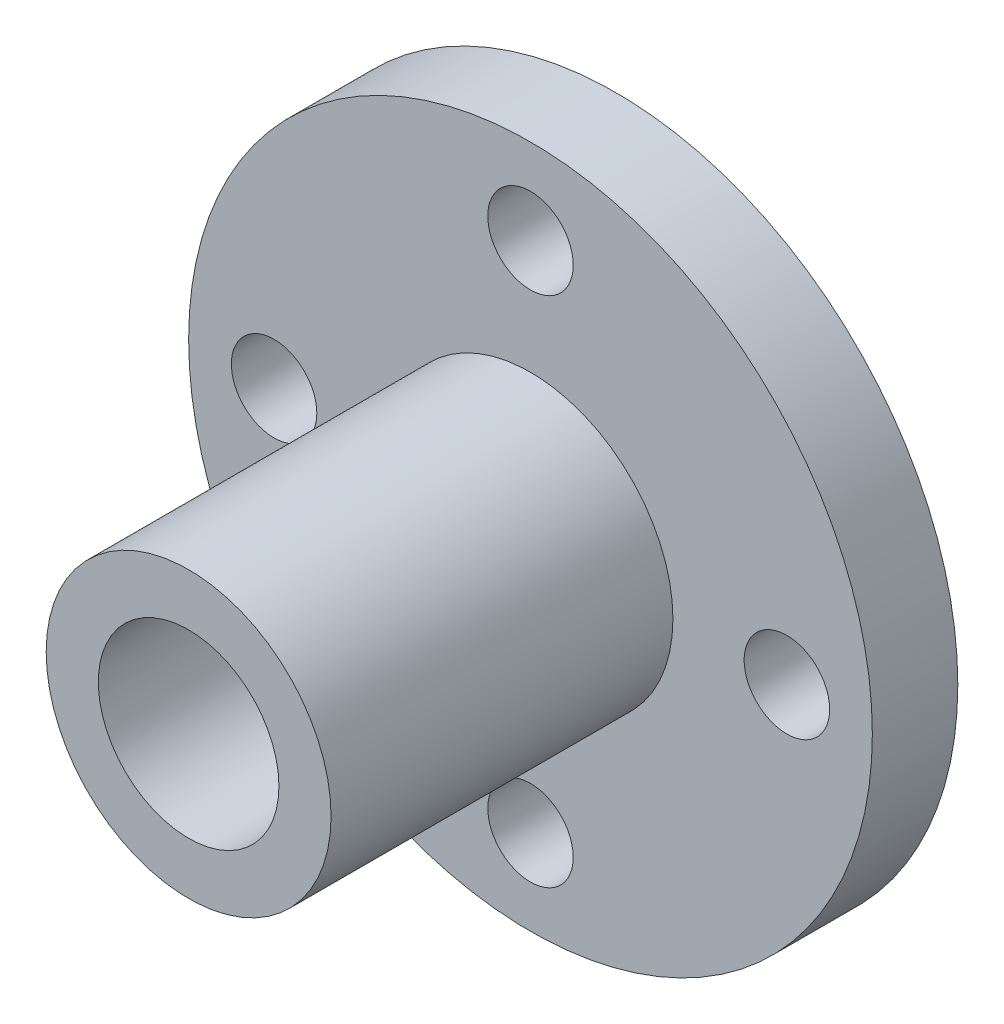
SolidWorks part; units mm, degrees
ref_plane "前视基准面" through (0, 0, 0) normal (0, 0, 1) x (1, 0, 0)
ref_plane "上视基准面" through (0, 0, 0) normal (0, 1, 0) x (1, 0, 0)
ref_plane "右视基准面" through (0, 0, 0) normal (1, 0, 0) x (0, 0, -1)
sketch "Sketch1" plane through (0, 0, 0) normal (0, 0, 1) x (1, 0, 0)
  circle A0 centre (0, 0) radius 12
extrude "Boss-Extrude1" add sketch "Sketch1" along normal blind 3
sketch "Sketch2" plane through (0, 0, 0) normal (0, 0, 1) x (1, 0, 0)
  circle A0 centre (0, 0) radius 5
extrude "Boss-Extrude2" add sketch "Sketch2" along normal blind 15
sketch "Sketch3" plane through (0, 0, 0) normal (0, 0, 1) x (1, 0, 0)
  circle A0 centre (0, 0) radius 3.17
extrude "Cut-Extrude1" cut sketch "Sketch3" along normal blind 15
sketch "Sketch4" plane through (0, 0, 0) normal (0, 0, 1) x (1, 0, 0)
  circle A0 centre (-9, 0) radius 1.5
  circle A1 centre (0, 9) radius 1.5
  circle A2 centre (9, 0) radius 1.5
  circle A3 centre (0, -9) radius 1.5
  point P12 (0, 0)
  dimension "D1" = 4
extrude "Cut-Extrude2" cut sketch "Sketch4" along normal blind 5
